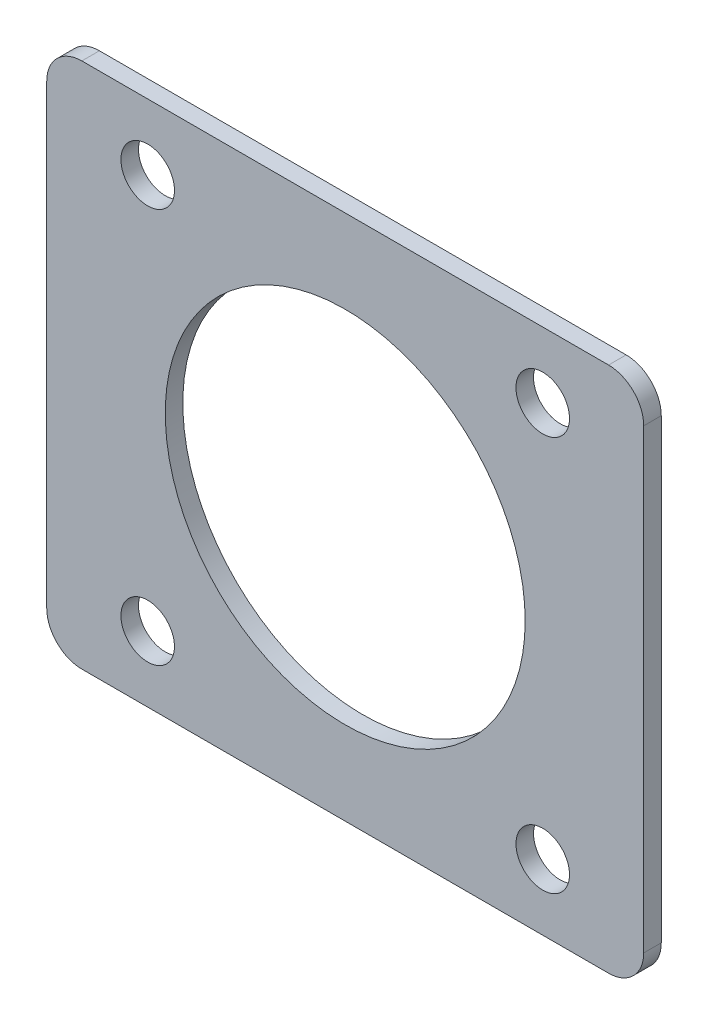
SolidWorks part; units mm, degrees
ref_plane "Front Plane" through (0, 0, 0) normal (0, 0, 1) x (1, 0, 0)
ref_plane "Top Plane" through (0, 0, 0) normal (0, 1, 0) x (1, 0, 0)
ref_plane "Right Plane" through (0, 0, 0) normal (1, 0, 0) x (0, 0, -1)
sketch "Sketch1" plane through (0, 0, 0) normal (0, 0, 1) x (1, 0, 0)
  line L0 (0, 0) -> (0, -40) construction
  line L2 (0, 0) -> (40.6669, 0) construction
  line L4 (-30, 30) -> (30, 30)
  line L5 (-34, 26) -> (-34, -26)
  line L6 (-30, -30) -> (30, -30)
  line L7 (34, 26) -> (34, -26)
  line L8 (-34, 30) -> (34, -30) construction
  line L9 (-34, -30) -> (34, 30) construction
  circle A0 centre (0, 0) radius 11.5022 construction
  circle A1 centre (22.5, -22.5) radius 3.05
  circle A3 centre (-22.5, -22.5) radius 3.05
  circle A4 centre (-22.5, 22.5) radius 3.05
  circle A5 centre (22.5, 22.5) radius 3.05
  circle A6 centre (0, 0) radius 20.5
  arc A7 (34, 26) -> (30, 30) centre (30, 26) ccw
  arc A8 (-30, 30) -> (-34, 26) centre (-30, 26) ccw
  arc A9 (-34, -26) -> (-30, -30) centre (-30, -26) ccw
  arc A10 (30, -30) -> (34, -26) centre (30, -26) ccw
  dimension "D1" = 6.1
  dimension "D2" = 41
  dimension "D3" = 4
  dimension "D6" = 23.0043
  dimension "D4" = 68
  dimension "D5" = 60
  dimension "D7" = 45
  dimension "D8" = 45
extrude "Boss-Extrude1" add sketch "Sketch1" along normal blind 2
